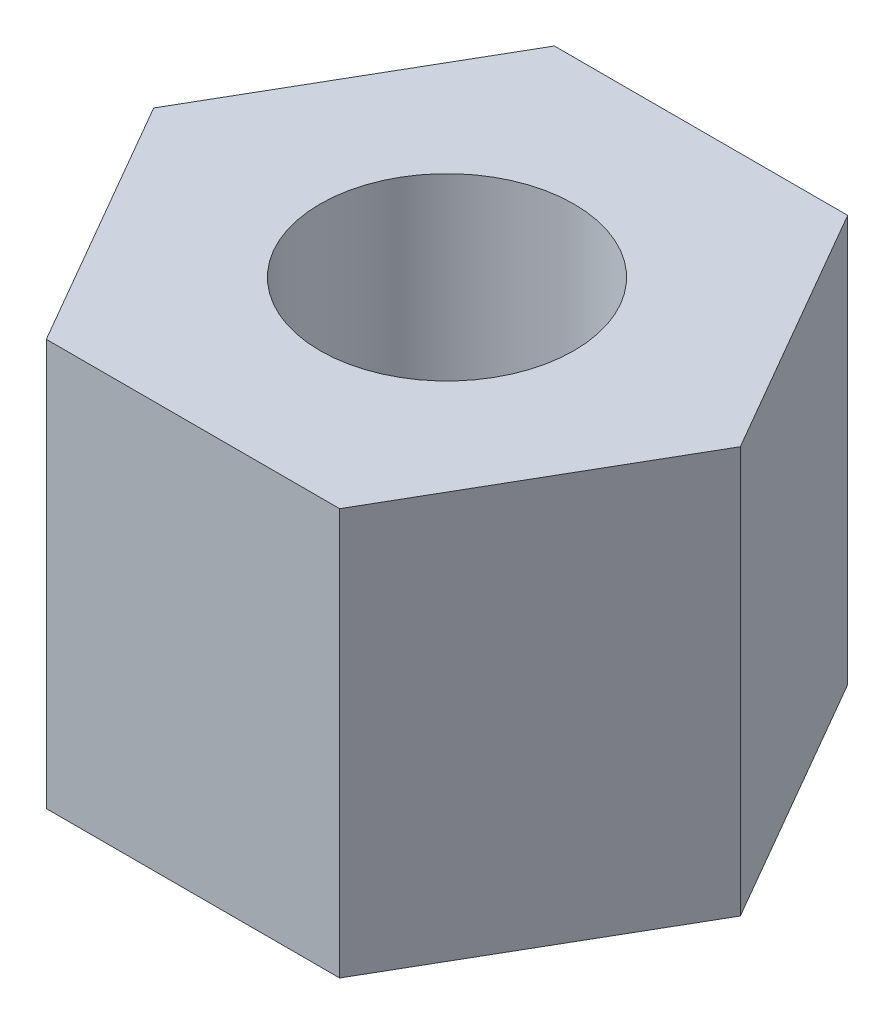
SolidWorks part; units mm, degrees
material "ABS"
ref_plane "前视基准面" through (0, 0, 0) normal (0, 0, 1) x (1, 0, 0)
ref_plane "上视基准面" through (0, 0, 0) normal (0, 1, 0) x (1, 0, 0)
ref_plane "右视基准面" through (0, 0, 0) normal (1, 0, 0) x (0, 0, -1)
sketch "草图1" plane through (0, 0, 0) normal (0, 1, 0) x (1, 0, 0)
  line L1 (1.4434, -2.5) -> (2.8868, 0)
  line L2 (2.8868, 0) -> (1.4434, 2.5)
  line L3 (1.4434, 2.5) -> (-1.4434, 2.5)
  line L4 (-1.4434, 2.5) -> (-2.8868, 0)
  line L5 (-2.8868, 0) -> (-1.4434, -2.5)
  line L6 (-1.4434, -2.5) -> (1.4434, -2.5)
  circle A0 centre (0, 0) radius 1.25
  circle A1 centre (0, 0) radius 2.5 construction
  dimension "D1" = 2.5
  dimension "D2" = 5
extrude "凸台-拉伸1" add sketch "草图1" along normal blind 4
